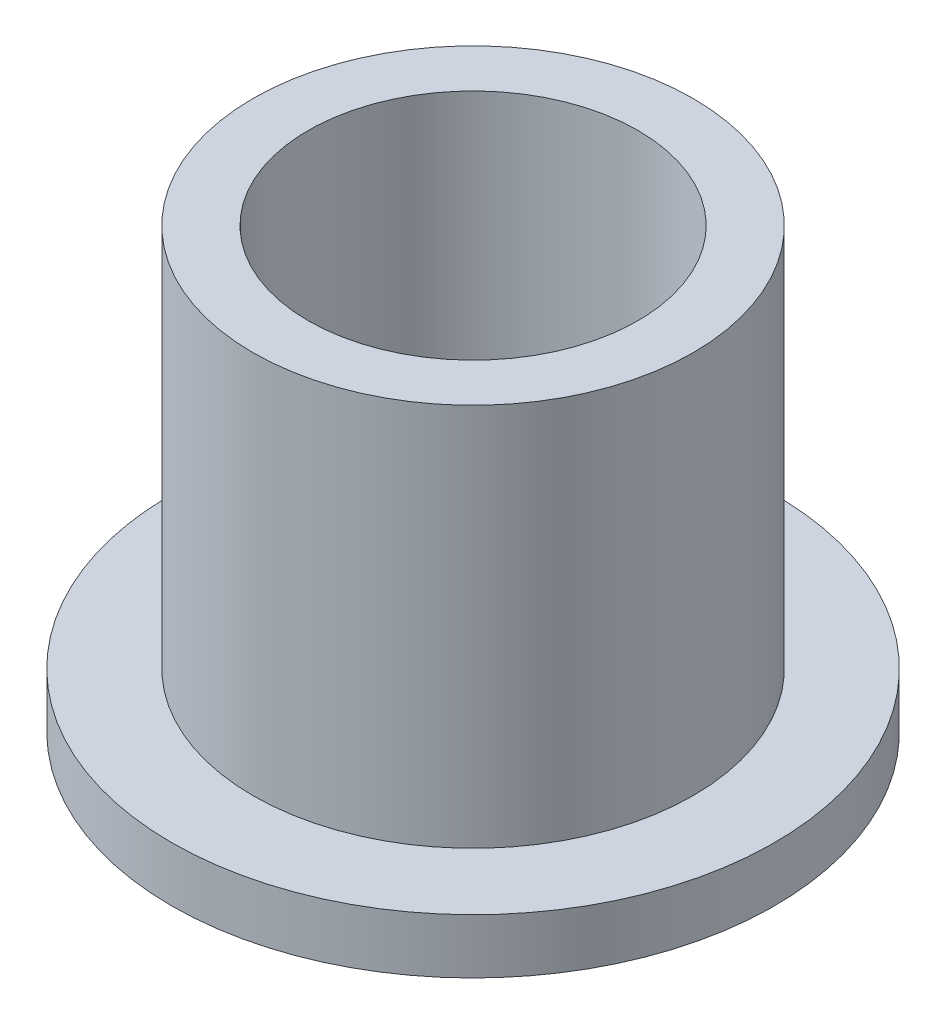
SolidWorks part; units mm, degrees
material "Manganese Bronze"
ref_plane "Front" through (0, 0, 0) normal (0, 0, 1) x (1, 0, 0)
ref_plane "Top" through (0, 0, 0) normal (0, 1, 0) x (1, 0, 0)
ref_plane "Right" through (0, 0, 0) normal (1, 0, 0) x (0, 0, -1)
sketch "Sketch1" plane through (0, 0, 0) normal (0, 1, 0) x (1, 0, 0)
  circle A0 centre (0, 0) radius 4.7752
  circle A1 centre (0, 0) radius 6.3754
  circle A2 centre (0, 0) radius 8.7312
  dimension "ID" = 9.5504
  dimension "OD" = 12.7508
  dimension "FlangeOD" = 17.4625
sketch "Sketch2" plane through (0, 0, 0) normal (0, 1, 0) x (1, 0, 0)
  circle A0 centre (0, 0) radius 4.7752 construction
  circle A1 centre (0, 0) radius 6.3754 construction
  circle A2 centre (0, 0) radius 4.7752
  circle A3 centre (0, 0) radius 6.3754
extrude "Boss-Extrude1" add sketch "Sketch2" along normal blind 12.7
sketch "Sketch3" plane through (0, 0, 0) normal (0, 1, 0) x (1, 0, 0)
  circle A0 centre (0, 0) radius 8.7312 construction
  circle A1 centre (0, 0) radius 6.3754 construction
  circle A2 centre (0, 0) radius 8.7312
  circle A3 centre (0, 0) radius 6.3754
extrude "Boss-Extrude2" add sketch "Sketch3" along normal blind 1.5875
